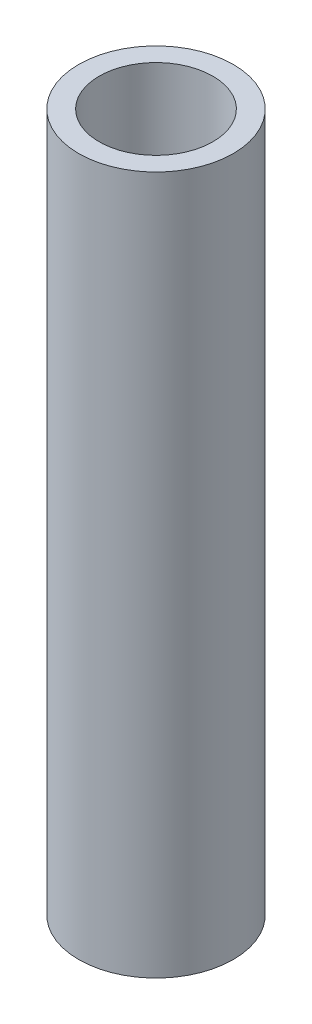
SolidWorks part; units mm, degrees
ref_plane "Top Plane" through (0, 0, 0) normal (0, 0, 1) x (1, 0, 0)
ref_plane "Front Plane" through (0, 0, 0) normal (0, 1, 0) x (1, 0, 0)
ref_plane "Right Plane" through (0, 0, 0) normal (1, 0, 0) x (0, 0, -1)
sketch "Sketch1" plane through (0, 0, 0) normal (0, 1, 0) x (1, 0, 0)
  circle A0 centre (0, 0) radius 4.0894
  circle A1 centre (0, 0) radius 5.5562
  dimension "D1" = 8.1788
  dimension "D2" = 11.1125
extrude "Boss-Extrude1" add sketch "Sketch1" along normal up to surface (50.2 mm away)
